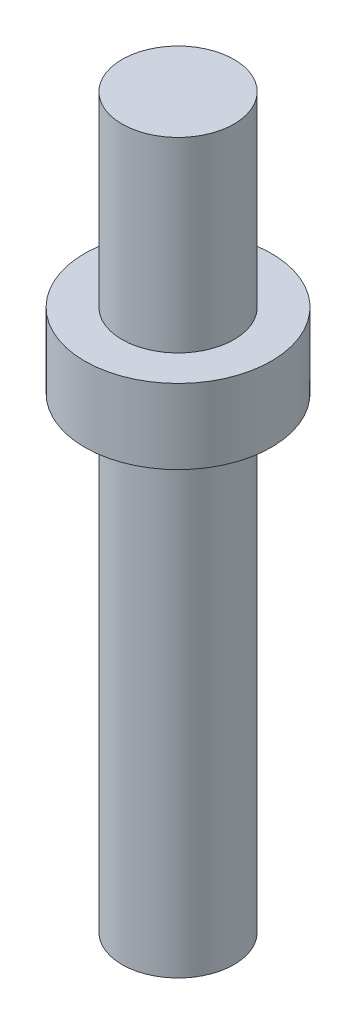
SolidWorks part; units mm, degrees
ref_plane "Front Plane" through (0, 0, 0) normal (0, 0, 1) x (1, 0, 0)
ref_plane "Top Plane" through (0, 0, 0) normal (0, 1, 0) x (1, 0, 0)
ref_plane "Right Plane" through (0, 0, 0) normal (1, 0, 0) x (0, 0, -1)
sketch "Sketch1" plane through (0, 0, 0) normal (0, 1, 0) x (1, 0, 0)
  circle A0 centre (0, 0) radius 1.5
  dimension "D1" = 3
extrude "Boss-Extrude1" add sketch "Sketch1" along normal blind 12.5
sketch "Sketch2" plane through (0, 12.5, 0) normal (0, 1, 0) x (1, 0, 0)
  circle A0 centre (0, 0) radius 2.5
  dimension "D1" = 5
extrude "Boss-Extrude2" add sketch "Sketch2" along normal blind 2
sketch "Sketch3" plane through (0, 14.5, 0) normal (0, 1, 0) x (1, 0, 0)
  circle A0 centre (0, 0) radius 1.5
  dimension "D1" = 3
extrude "Boss-Extrude3" add sketch "Sketch3" along normal blind 5
